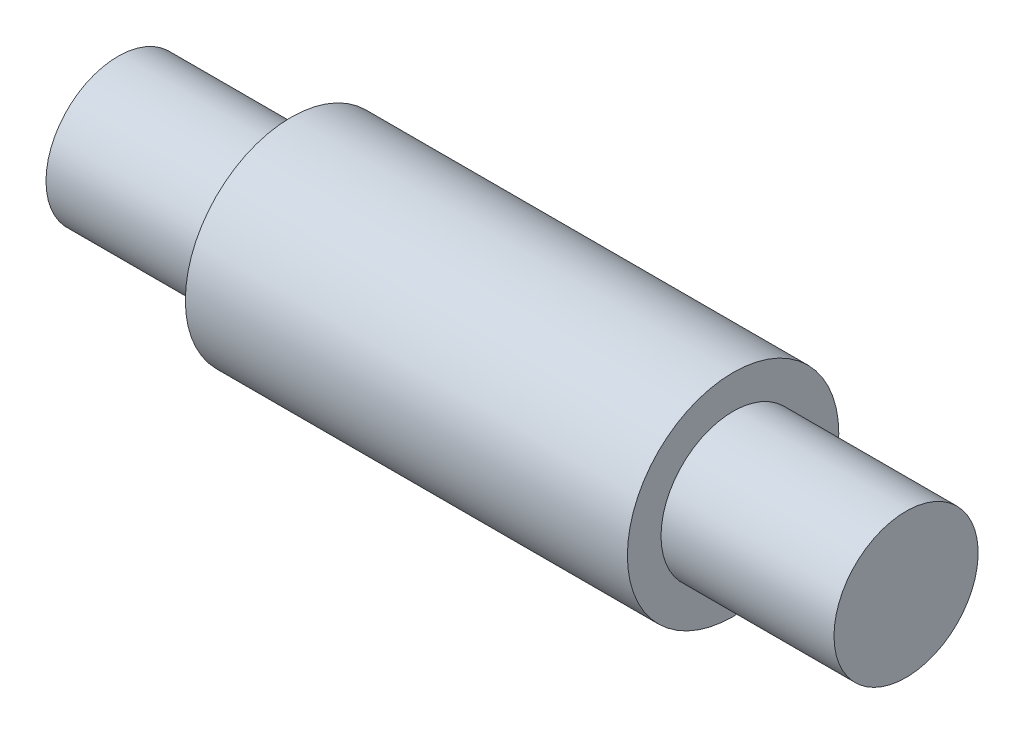
SolidWorks part; units mm, degrees
ref_plane "Front Plane" through (0, 0, 0) normal (0, 0, 1) x (1, 0, 0)
ref_plane "Top Plane" through (0, 0, 0) normal (0, 1, 0) x (1, 0, 0)
ref_plane "Right Plane" through (0, 0, 0) normal (1, 0, 0) x (0, 0, -1)
sketch "Sketch1" plane through (0, 0, 0) normal (0, 0, 1) x (1, 0, 0)
  line L0 (-59.345, 0) -> (22.655, 0)
  line L1 (-59.345, 0) -> (-59.345, 7.5)
  line L2 (-59.345, 7.5) -> (-41.345, 7.5)
  line L3 (-41.345, 7.5) -> (-41.345, 11)
  line L4 (-41.345, 11) -> (4.655, 11)
  line L5 (4.655, 11) -> (4.655, 7.5)
  line L6 (4.655, 7.5) -> (22.655, 7.5)
  line L7 (22.655, 7.5) -> (22.655, 0)
  dimension "D1" = 82
  dimension "D2" = 7.5
  dimension "D3" = 18
  dimension "D4" = 3.5
  dimension "D5" = 46
  dimension "D6" = 3.5
  dimension "D7" = 18
  dimension "D8" = 7.5
revolve "Revolve1" add sketch "Sketch1" angle 360 about L0
cosmetic thread "Cosmetic Thread1" parameters "D1"=13, "D2"=11.797
cosmetic thread "Cosmetic Thread2" parameters "D1"=13, "D2"=11.797
